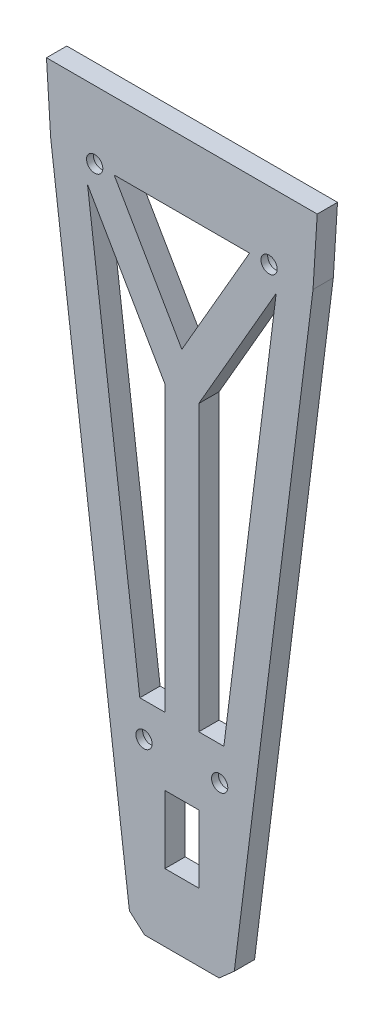
SolidWorks part; units mm, degrees
ref_plane "Front" through (0, 0, 0) normal (0, 0, 1) x (1, 0, 0)
ref_plane "Top" through (0, 0, 0) normal (0, 1, 0) x (1, 0, 0)
ref_plane "Right" through (0, 0, 0) normal (1, 0, 0) x (0, 0, -1)
sketch "草图1" plane through (0, 0, 0) normal (0, 0, 1) x (1, 0, 0)
  line L0 (20, 5) -> (20, 45)
  line L1 (-7.5, 100) -> (-13.2417, 95.0553)
  line L2 (-13.2417, 95.0553) -> (-19.2583, 54.9447)
  line L3 (7.5, 100) -> (13.2417, 95.0553)
  line L4 (-20, 5) -> (-20, 45)
  line L5 (7.5, 100) -> (-7.5, 100)
  line L6 (13.2417, 95.0553) -> (19.2583, 54.9447)
  line L7 (-19.2583, 54.9447) -> (-20, 45)
  line L8 (5.5, -100) -> (-5.5, -100)
  line L9 (-7.7481, -98.0154) -> (-19.3798, -4.9614)
  line L10 (19.3798, -4.9614) -> (7.7481, -98.0154)
  line L11 (19.2583, 54.9447) -> (20, 45)
  line L12 (-19.3798, -4.9614) -> (-20, 5)
  line L13 (19.3798, -4.9614) -> (20, 5)
  line L14 (-5.5, -100) -> (-7.7481, -98.0154)
  line L15 (7.7481, -98.0154) -> (5.5, -100)
  point P1 (-20, 50)
  point P3 (-20, 0)
  point P5 (20, 0)
  point P6 (20, 50)
  point P8 (12.5, 100)
  point P9 (-12.5, 100)
  point P10 (7.5, -100)
  point P12 (-7.5, -100)
extrude "凸台-拉伸1" add sketch "草图1" along normal blind 3
sketch "草图2" plane through (0, 0, 3) normal (0, 0, 1) x (1, 0, 0)
  line L0 (0, 0) -> (0, -100) construction
  line L1 (-5.5, -100) -> (5.5, -100) construction
  line L2 (10, -5) -> (-10, -5)
  line L3 (-10, -5) -> (0, -22.3205)
  line L4 (0, -22.3205) -> (10, -5)
  line L5 (-5.5, -100) -> (5.5, -100) construction
  line L12 (2.7867, -97.3953) -> (14.4184, -4.3412)
  line L13 (6.2111, -70) -> (13.9389, -8.1777)
  line L14 (-13.9389, -8.1777) -> (-2.5, -27.9904)
  line L15 (-14.4184, -4.3412) -> (-2.7867, -97.3953)
  line L16 (-13.9389, -8.1777) -> (-6.2111, -70)
  line L17 (2.5, -27.9904) -> (13.9389, -8.1777)
  line L18 (6.2111, -70) -> (2.5, -70)
  line L19 (2.5, -27.9904) -> (2.5, -70)
  line L20 (2.5, 0) -> (2.5, -100) construction
  line L21 (4.3301, -24.8205) -> (14.3301, -7.5) construction
  line L22 (10, -70) -> (-10, -70) construction
  line L23 (-2.5, -27.9904) -> (-2.5, -70)
  line L24 (-14.3301, -7.5) -> (-4.3301, -24.8205) construction
  line L25 (-2.5, -70) -> (-6.2111, -70)
  line L26 (2.5, -90) -> (2.5, -80)
  line L27 (2.5, -90) -> (-2.5, -90)
  line L29 (2.5, -80) -> (-2.5, -80)
  line L30 (-2.5, -90) -> (-2.5, -80)
  point P8 (0, -5)
  point P34 (0, -90)
  point P35 (0, -80)
  dimension "D1" = 5
  dimension "D2" = 5
  dimension "D9" = 10
  dimension "D3" = 5
  dimension "D4" = 5
  dimension "D5" = 5
  dimension "D6" = 65
  dimension "D7" = 2.5
  dimension "D8" = 5
extrude "切除-拉伸1" cut sketch "草图2" against normal up to next
sketch "草图3" plane through (0, 0, 0) normal (0, 0, -1) x (-1, 0, 0)
  point P0 (-5.5861, -75)
  point P1 (5.5861, -75)
hole_wizard "M2 凹头盖螺钉的柱形沉头孔1" positions "3D草图1" profile "草图4" counterbore size "M2" standard "ANSI Metric" end condition through all
sketch3d "3D草图1"
  point P0 (5.5861, -75, 0)
  point P3 (-5.5861, -75, 0)
sketch "草图4" plane through (5.5861, -75, 0) normal (1, 0, 0) x (0, 1, 0)
  line L0 (0, 0) -> (0, 3)
  line L1 (0, 3) -> (1.2, 3)
  line L3 (1.2, 3) -> (1.2, 2)
  line L4 (1.2, 2) -> (2.2, 2)
  line L5 (2.2, 2) -> (2.2, 0)
  line L7 (2.2, 0) -> (0, 0)
  line L11 (0, -6.35) -> (0, 107.95) construction
  dimension "通孔孔直径" = 2.4
  dimension "通孔孔深度" = 3
  dimension "柱形沉头孔直径" = 4.4
  dimension "柱形沉头孔深度" = 2
sketch "草图5" plane through (0, 0, 0) normal (0, 0, -1) x (-1, 0, 0)
  line L0 (-20, 25) -> (20, 25) construction
  line L1 (-20, 5) -> (-20, 45) construction
  line L2 (20, 45) -> (20, 5) construction
  circle A0 centre (0, 25) radius 4
extrude "切除-拉伸2" cut sketch "草图5" against normal up to next
sketch "草图6" plane through (0, 0, 0) normal (0, 0, -1) x (-1, 0, 0)
  point P0 (-8, 25)
  point P1 (0, 33)
  point P2 (8, 25)
  point P3 (0, 17)
  point P4 (0, 25)
  dimension "D1" = 8
  dimension "D2" = 8
  dimension "D3" = 8
  dimension "D4" = 8
hole_wizard "M2 凹头盖螺钉的柱形沉头孔2" positions "3D草图2" profile "草图7" counterbore size "M2" standard "ANSI Metric" end condition through all
sketch3d "3D草图2"
  point P0 (8, 25, 0)
  point P3 (0, 33, 0)
  point P6 (-8, 25, 0)
  point P9 (0, 17, 0)
sketch "草图7" plane through (8, 25, 0) normal (1, 0, 0) x (0, 1, 0)
  line L0 (0, 0) -> (0, 3)
  line L1 (0, 3) -> (1.2, 3)
  line L3 (1.2, 3) -> (1.2, 2)
  line L4 (1.2, 2) -> (2.2, 2)
  line L5 (2.2, 2) -> (2.2, 0)
  line L7 (2.2, 0) -> (0, 0)
  line L11 (0, -6.35) -> (0, 107.95) construction
  dimension "通孔孔直径" = 2.4
  dimension "通孔孔深度" = 3
  dimension "柱形沉头孔直径" = 4.4
  dimension "柱形沉头孔深度" = 2
sketch "草图8" plane through (0, 0, 0) normal (0, 0, -1) x (-1, 0, 0)
  line L0 (0, -3.3014) -> (0, -6.7473) construction
  point P2 (12.88, -5.0117)
  point P3 (-12.88, 14.9883)
  point P4 (12.88, 14.9883)
  point P12 (-12.88, -5.0117)
  dimension "D1" = 20
  dimension "D2" = 20
hole_wizard "M2 凹头盖螺钉的柱形沉头孔3" positions "3D草图3" profile "草图9" counterbore size "M2" standard "ANSI Metric" end condition through all
sketch3d "3D草图3"
  point P0 (12.88, -5.0117, 0)
  point P3 (-12.88, -5.0117, 0)
sketch "草图9" plane through (12.88, -5.0117, 0) normal (1, 0, 0) x (0, 1, 0)
  line L0 (0, 0) -> (0, 3)
  line L1 (0, 3) -> (1.2, 3)
  line L3 (1.2, 3) -> (1.2, 2)
  line L4 (1.2, 2) -> (2.2, 2)
  line L5 (2.2, 2) -> (2.2, 0)
  line L7 (2.2, 0) -> (0, 0)
  line L11 (0, -6.35) -> (0, 107.95) construction
  dimension "通孔孔直径" = 2.4
  dimension "通孔孔深度" = 3
  dimension "柱形沉头孔直径" = 4.4
  dimension "柱形沉头孔深度" = 2
sketch "草图10" plane through (0, 0, 0) normal (0, 0, -1) x (-1, 0, 0)
  line L0 (-9.5291, 85.3364) -> (-1.6465, 83.9709) construction
  line L1 (9.5291, 85.3364) -> (1.6465, 83.9709) construction
  line L2 (-14.3136, 54.203) -> (-8.297, 94.3136)
  line L3 (-14.0169, 56.1809) -> (-10.6793, 78.4319)
  line L4 (-9.344, 87.3336) -> (-8.297, 94.3136)
  line L5 (8.297, 94.3136) -> (14.3136, 54.203)
  line L6 (8.297, 94.3136) -> (9.344, 87.3336)
  line L7 (-8.297, 94.3136) -> (0, 94.3136)
  line L8 (-12.3136, 54.203) -> (-4.5, 54.203)
  line L9 (0, 95.3482) -> (0, 43.337) construction
  line L10 (-2.5, 77.0442) -> (-2.5, 56.203)
  line L11 (-9.344, 87.3336) -> (-7.6701, 85.0144)
  line L12 (9.344, 87.3336) -> (7.6701, 85.0144)
  line L13 (-10.3826, 80.4098) -> (-2.5, 79.0442) construction
  line L14 (-10.6793, 78.4319) -> (-8.4119, 80.0684)
  line L15 (4.5, 54.203) -> (12.3136, 54.203)
  line L16 (-8.4119, 80.0684) -> (-4.4706, 79.3856)
  line L17 (8.4119, 80.0684) -> (4.4706, 79.3856)
  line L18 (-7.6701, 85.0144) -> (0, 83.6856)
  line L19 (7.6701, 85.0144) -> (0, 83.6856)
  line L20 (0, 94.3136) -> (8.297, 94.3136)
  line L21 (-4.4706, 79.3856) -> (-2.5, 77.0442)
  line L22 (2.5, 77.0442) -> (2.5, 56.203)
  line L23 (10.6793, 78.4319) -> (14.0169, 56.1809)
  line L24 (10.3826, 80.4098) -> (2.5, 79.0442) construction
  line L25 (4.4706, 79.3856) -> (2.5, 77.0442)
  line L26 (10.6793, 78.4319) -> (8.4119, 80.0684)
  line L27 (-12.3136, 54.203) -> (-14.0169, 56.1809)
  line L28 (-4.5, 54.203) -> (-2.5, 56.203)
  line L29 (2.5, 56.203) -> (4.5, 54.203)
  line L30 (12.3136, 54.203) -> (14.0169, 56.1809)
  point P16 (-2.5, 54.203)
  point P17 (2.5, 54.203)
  point P18 (-10.3826, 80.4098)
  point P26 (-9.6407, 85.3557)
  point P28 (9.6407, 85.3557)
  dimension "D3" = 26.5
  dimension "D6" = 5
  dimension "D1" = 5
  dimension "D2" = 5
  dimension "D7" = 5
extrude "切除-拉伸3" cut sketch "草图10" against normal blind 3
sketch "草图11" plane through (0, 0, 0) normal (0, 0, -1) x (-1, 0, 0)
  point P11 (0, 79.8401)
hole_wizard "M2 凹头盖螺钉的柱形沉头孔5" positions "3D草图5" profile "草图13" counterbore size "M2" standard "ANSI Metric" end condition through all
sketch3d "3D草图5"
  point P0 (0, 79.8401, 0)
sketch "草图13" plane through (0, 79.8401, 0) normal (1, 0, 0) x (0, 1, 0)
  line L0 (0, 0) -> (0, 3)
  line L1 (0, 3) -> (1.2, 3)
  line L3 (1.2, 3) -> (1.2, 2)
  line L4 (1.2, 2) -> (2.2, 2)
  line L5 (2.2, 2) -> (2.2, 0)
  line L7 (2.2, 0) -> (0, 0)
  line L11 (0, -6.35) -> (0, 107.95) construction
  dimension "通孔孔直径" = 2.4
  dimension "通孔孔深度" = 3
  dimension "柱形沉头孔直径" = 4.4
  dimension "柱形沉头孔深度" = 2
hole_wizard "M2 凹头盖螺钉的柱形沉头孔6" positions "3D草图8" profile "草图16" counterbore size "M2" standard "ANSI Metric" end condition up to next
sketch3d "3D草图8"
  point P0 (12.88, 14.9883, 0)
  point P3 (-12.88, 14.9883, 0)
sketch "草图16" plane through (12.88, 14.9883, 0) normal (1, 0, 0) x (0, 1, 0)
  line L0 (0, 0) -> (0, 3)
  line L1 (0, 3) -> (1.2, 3)
  line L3 (1.2, 3) -> (1.2, 2)
  line L4 (1.2, 2) -> (2.2, 2)
  line L5 (2.2, 2) -> (2.2, 0)
  line L7 (2.2, 0) -> (0, 0)
  line L11 (0, -6.35) -> (0, 107.95) construction
  dimension "通孔孔直径" = 2.4
  dimension "通孔孔深度" = 3
  dimension "柱形沉头孔直径" = 4.4
  dimension "柱形沉头孔深度" = 2
sketch "草图17" plane through (0, 0, 0) normal (0, 0, -1) x (-1, 0, 0)
  line L0 (-20, 5) -> (20, 5)
  line L1 (-20, 5) -> (-20, 99.9983)
  line L2 (20, 5) -> (20, 99.9983)
  line L3 (-7.5, 100) -> (7.5, 100) construction
  line L4 (20, 5) -> (19.3798, -4.9614) construction
  line L5 (-7.5, 100) -> (7.5, 100)
  line L6 (-7.5, 100) -> (-20, 99.9983)
  line L7 (7.5, 100) -> (20, 99.9983)
extrude "切除-拉伸4" cut sketch "草图17" against normal blind 10
